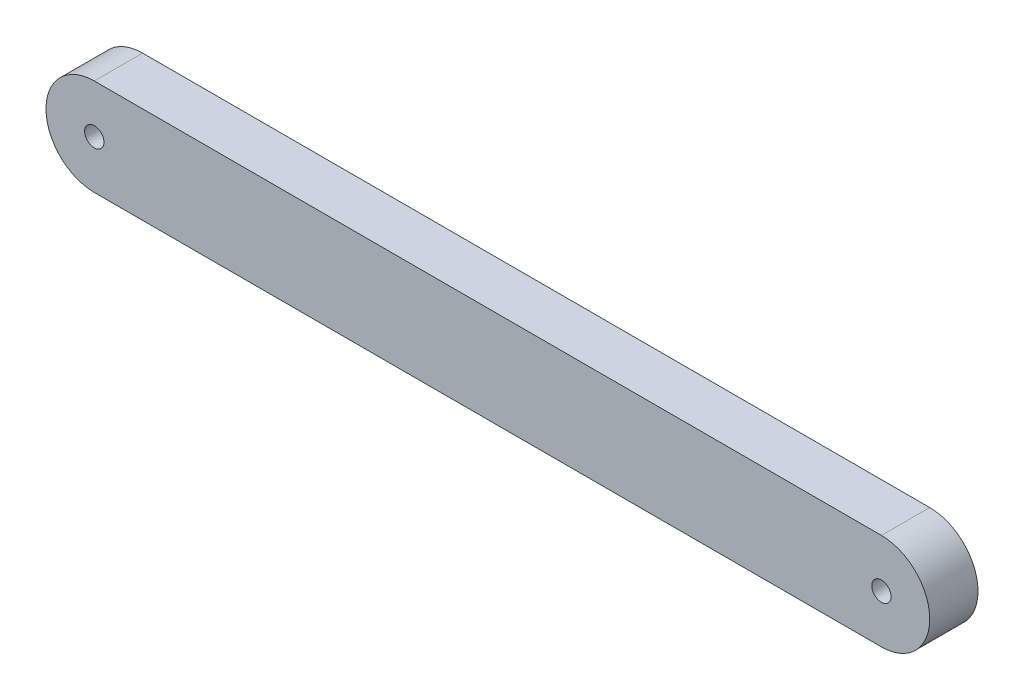
SolidWorks part; units mm, degrees
ref_plane "Front Plane" through (0, 0, 0) normal (0, 0, 1) x (1, 0, 0)
ref_plane "Top Plane" through (0, 0, 0) normal (0, 1, 0) x (1, 0, 0)
ref_plane "Right Plane" through (0, 0, 0) normal (1, 0, 0) x (0, 0, -1)
sketch "Sketch1" plane through (0, 0, 0) normal (0, 0, 1) x (1, 0, 0)
  line L0 (-30.2328, 7.5042) -> (-193.2328, 7.5042) construction
  line L1 (-30.2328, -2.4958) -> (-193.2328, -2.4958)
  line L2 (-30.2328, 17.5042) -> (-193.2328, 17.5042)
  arc A0 (-30.2328, -2.4958) -> (-30.2328, 17.5042) centre (-30.2328, 7.5042) ccw
  arc A1 (-193.2328, 17.5042) -> (-193.2328, -2.4958) centre (-193.2328, 7.5042) ccw
  circle A2 centre (-193.2328, 7.5042) radius 2
  circle A3 centre (-30.2328, 7.5042) radius 2
  point P2 (-111.7328, 7.5042)
  dimension "D2" = 10
  dimension "D1" = 163
extrude "Boss-Extrude1" add sketch "Sketch1" along normal blind 10
